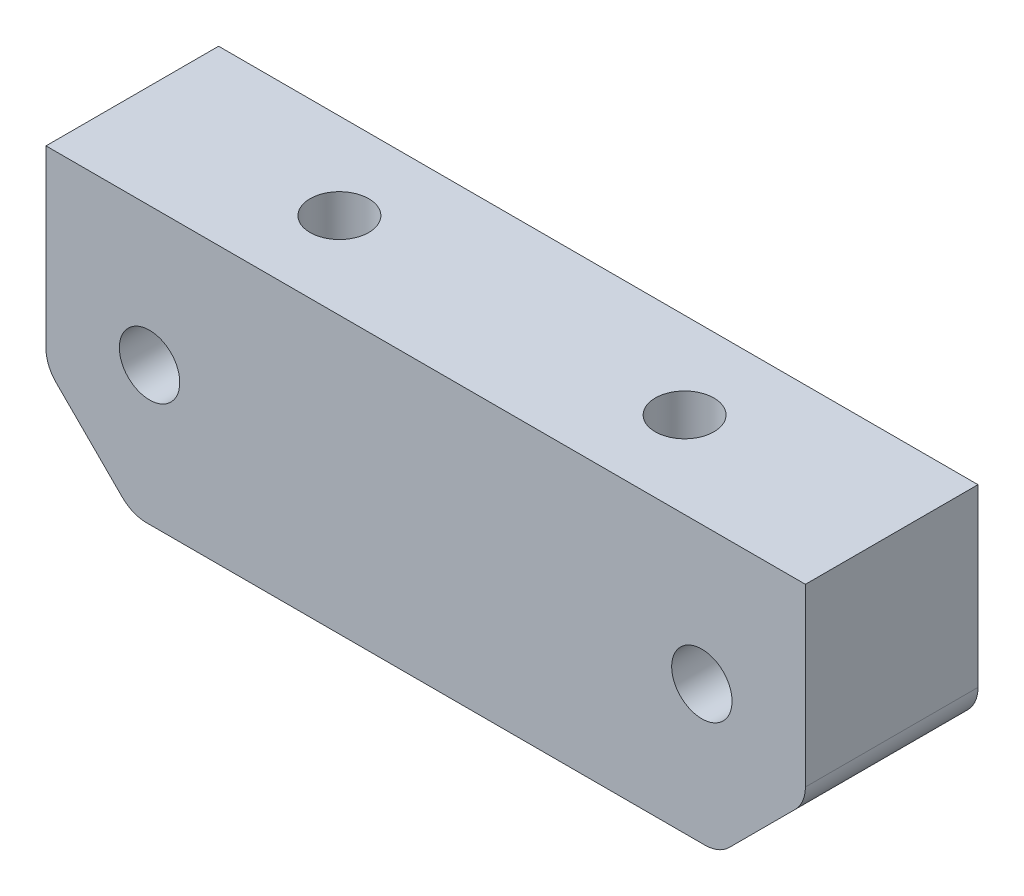
SolidWorks part; units mm, degrees
ref_plane "Front Plane" through (0, 0, 0) normal (0, 0, 1) x (1, 0, 0)
ref_plane "Top Plane" through (0, 0, 0) normal (0, 1, 0) x (1, 0, 0)
ref_plane "Right Plane" through (0, 0, 0) normal (1, 0, 0) x (0, 0, -1)
sketch "Sketch1" plane through (0, 0, 0) normal (0, 0, 1) x (1, 0, 0)
  line L1 (-22, -8) -> (22, -8)
  line L2 (-22, -8) -> (-22, 8)
  line L3 (-22, 8) -> (22, 8)
  line L4 (22, -8) -> (22, 8)
  line L5 (-22, -8) -> (22, 8) construction
  line L6 (-22, 8) -> (22, -8) construction
  point P0 (0, 0)
  dimension "D1" = 44
  dimension "D2" = 16
extrude "Boss-Extrude1" add sketch "Sketch1" along normal blind 10
sketch "Sketch2" plane through (0, -8, 0) normal (0, -1, 0) x (1, 0, 0)
  line L0 (0, 10) -> (0, 0) construction
  line L1 (-22, 10) -> (22, 10) construction
  line L2 (0, 5) -> (-10, 5) construction
  circle A0 centre (-10, 5) radius 1.7
  circle A1 centre (10, 5) radius 1.7
  dimension "D1" = 3.4
  dimension "D2" = 10
extrude "Cut-Extrude1" cut sketch "Sketch2" against normal blind 25
sketch "Sketch3" plane through (0, 0, 10) normal (0, 0, 1) x (1, 0, 0)
  line L0 (-10, 8) -> (-10, -8) construction
  line L1 (22, 8) -> (-22, 8) construction
  line L2 (-22, -8) -> (22, -8) construction
  line L3 (-10, 0) -> (-22, 0) construction
  line L4 (-22, 8) -> (-22, -8) construction
  line L5 (0, 8) -> (0, -8) construction
  circle A0 centre (-16, 0) radius 1.75
  circle A1 centre (16, 0) radius 1.75
  dimension "D2" = 3.5
  dimension "D1" = 10
extrude "Cut-Extrude2" cut sketch "Sketch3" against normal blind 25
chamfer "Chamfer1" distance 5 angle 45 2 edges at (22, -8, 5) (-22, -8, 5)
fillet "Fillet1" radius 2 4 edges at (22, -3, 5) (17, -8, 5) (-17, -8, 5) (-22, -3, 5)
sketch "Sketch4" plane through (0, -8, 0) normal (0, -1, 0) x (1, 0, 0)
  circle A0 centre (10, 5) radius 3.5
  circle A1 centre (-10, 5) radius 3.5
  dimension "D1" = 7
  dimension "D2" = 7
extrude "Cut-Extrude3" cut sketch "Sketch4" against normal blind 4
